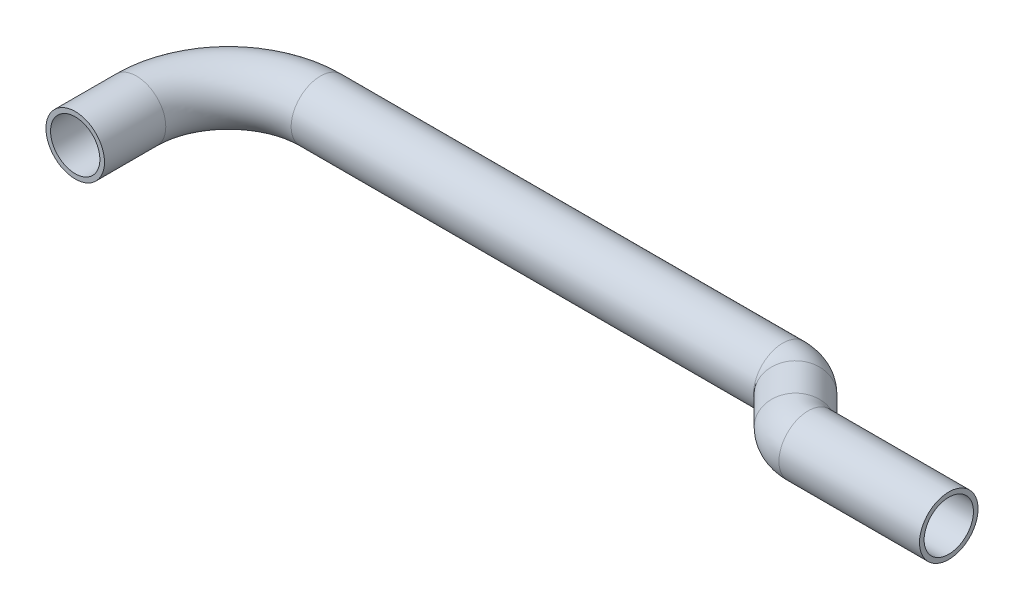
SolidWorks part; units mm, degrees
ref_plane "Front Plane" through (0, 0, 0) normal (0, 0, 1) x (1, 0, 0)
ref_plane "Top Plane" through (0, 0, 0) normal (0, 1, 0) x (1, 0, 0)
ref_plane "Right Plane" through (0, 0, 0) normal (1, 0, 0) x (0, 0, -1)
sketch "Sketch1" plane through (0, 0, 0) normal (0, 1, 0) x (1, 0, 0)
  line L1 (30, 50) -> (180.8579, 50)
  line L2 (187.9289, 47.0711) -> (197.0711, 37.9289)
  line L3 (204.1421, 35) -> (250, 35)
  line L4 (0, -55) -> (0, 55) construction
  line L5 (0, 20) -> (0, 0)
  line L6 (-55, 0) -> (55, 0) construction
  arc A0 (0, 20) -> (30, 50) centre (30, 20) cw
  arc A1 (180.8579, 50) -> (187.9289, 47.0711) centre (180.8579, 40) cw
  arc A2 (197.0711, 37.9289) -> (204.1421, 35) centre (204.1421, 45) ccw
  point P16 (200, 35)
  dimension "D1" = 250
  dimension "D4" = 30
  dimension "D7" = 10
  dimension "D2" = 50
  dimension "D3" = 15
  dimension "D5" = 50
  dimension "D6" = 45
sketch "Sketch2" plane through (0, 0, 0) normal (0, 0, 1) x (1, 0, 0)
  circle A0 centre (0, 0) radius 9.55
  circle A1 centre (0, 0) radius 8.05
  dimension "D1" = 19.1
  dimension "D2" = 1.5
sweep "Sweep1" add profiles "Sketch2" path "Sketch1"
